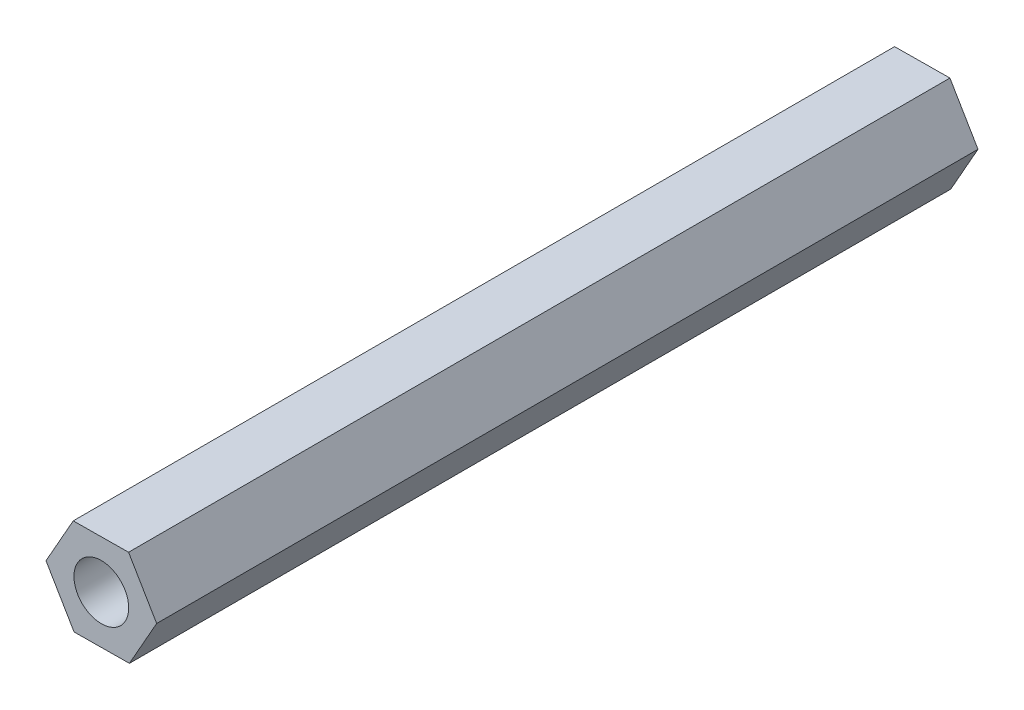
SolidWorks part; units mm, degrees
ref_plane "前视基准面" through (0, 0, 0) normal (0, 0, 1) x (1, 0, 0)
ref_plane "上视基准面" through (0, 0, 0) normal (0, 1, 0) x (1, 0, 0)
ref_plane "右视基准面" through (0, 0, 0) normal (1, 0, 0) x (0, 0, -1)
sketch "草图1" plane through (0, 0, 0) normal (0, 0, 1) x (1, 0, 0)
  line L1 (2.0515, -3.4821) -> (4.0413, 0.0356)
  line L2 (4.0413, 0.0356) -> (1.9898, 3.5177)
  line L3 (1.9898, 3.5177) -> (-2.0515, 3.4821)
  line L4 (-2.0515, 3.4821) -> (-4.0413, -0.0356)
  line L5 (-4.0413, -0.0356) -> (-1.9898, -3.5177)
  line L6 (-1.9898, -3.5177) -> (2.0515, -3.4821)
  circle A0 centre (0, 0) radius 3.5 construction
  circle A1 centre (0, 0) radius 2
extrude "凸台-拉伸1" add sketch "草图1" along normal blind 60
